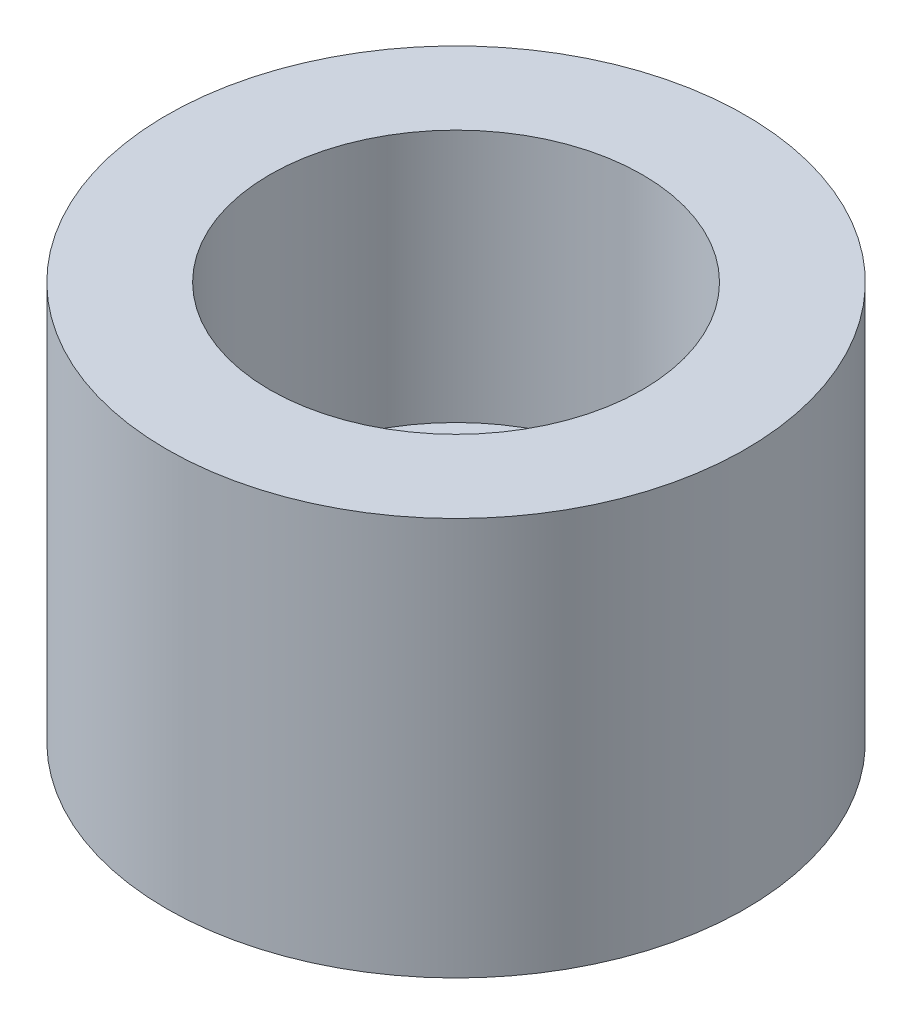
SolidWorks part; units mm, degrees
ref_plane "前视基准面" through (0, 0, 0) normal (0, 0, 1) x (1, 0, 0)
ref_plane "上视基准面" through (0, 0, 0) normal (0, 1, 0) x (1, 0, 0)
ref_plane "右视基准面" through (0, 0, 0) normal (1, 0, 0) x (0, 0, -1)
other "Configuration Table"
sketch "草图1" plane through (0, 0, 0) normal (0, 1, 0) x (1, 0, 0)
  circle A0 centre (0, 0) radius 8
  circle A1 centre (0, 0) radius 1.65
  dimension "D1" = 16
  dimension "D2" = 3.3
extrude "凸台-拉伸1" add sketch "草图1" along normal blind 4
sketch "草图2" plane through (0, 4, 0) normal (0, 1, 0) x (1, 0, 0)
  circle A0 centre (0, 0) radius 5.15
  circle A1 centre (0, 0) radius 8
  circle A2 centre (0, 0) radius 8
  dimension "D2" = 10.3
  dimension "D1" = 0
extrude "凸台-拉伸2" add sketch "草图2" along normal blind 7
